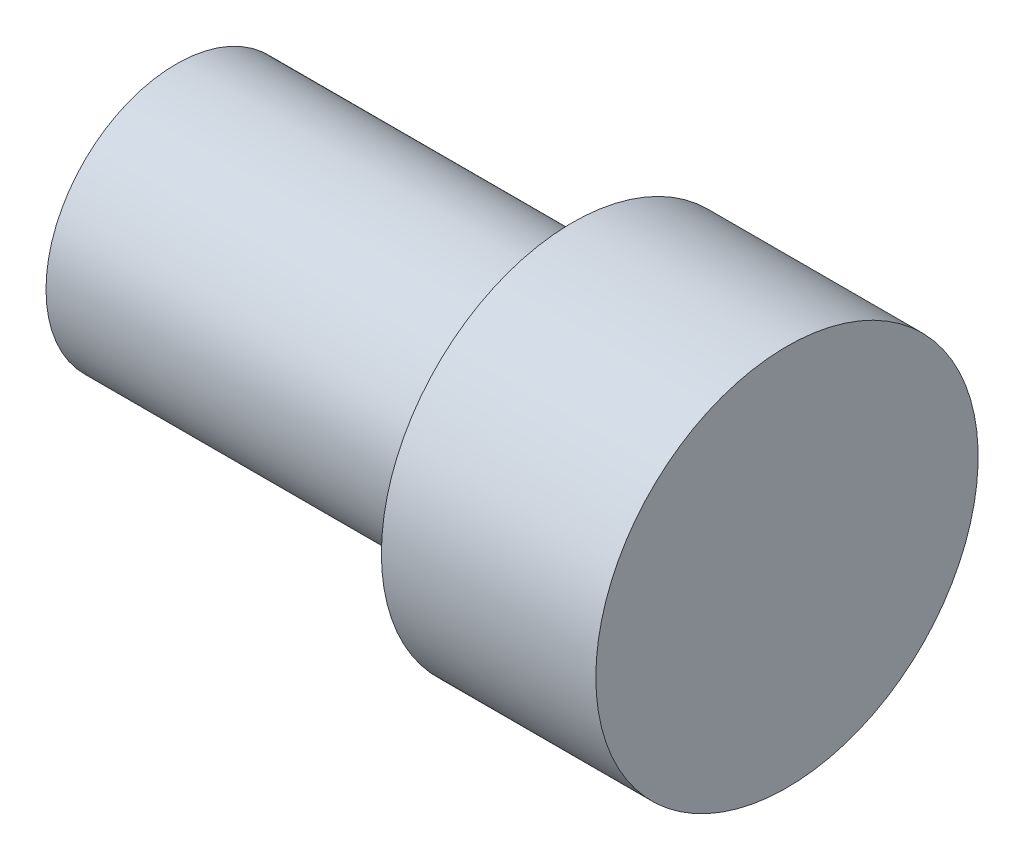
SolidWorks part; units mm, degrees
ref_plane "Plan de face" through (0, 0, 0) normal (0, 0, 1) x (1, 0, 0)
ref_plane "Plan de dessus" through (0, 0, 0) normal (0, 1, 0) x (1, 0, 0)
ref_plane "Plan de droite" through (0, 0, 0) normal (1, 0, 0) x (0, 0, -1)
sketch "Esquisse2" plane through (0, 0, 0) normal (0, 0, 1) x (1, 0, 0)
  line L0 (-65.9159, 0) -> (-65.9159, 28.0596)
  line L1 (-65.9159, 28.0596) -> (19.4724, 28.0596)
  line L2 (19.4724, 28.0596) -> (19.4724, 41.1886)
  line L3 (19.4724, 41.1886) -> (65.6741, 41.1886)
  line L4 (65.6741, 41.1886) -> (65.6741, 0)
  line L5 (-65.9159, 0) -> (65.6741, 0)
revolve "Révolution1" add sketch "Esquisse2" angle 360 about L5
